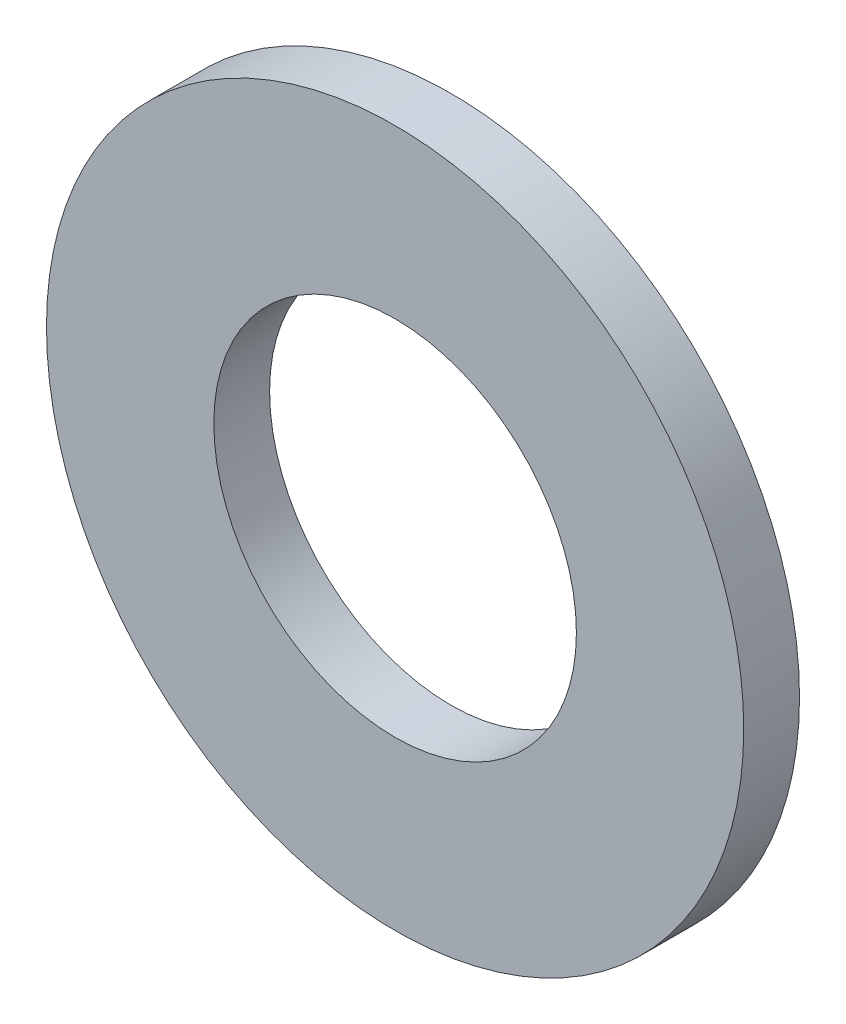
SolidWorks part; units mm, degrees
ref_plane "前视基准面" through (0, 0, 0) normal (0, 0, 1) x (1, 0, 0)
ref_plane "上视基准面" through (0, 0, 0) normal (0, 1, 0) x (1, 0, 0)
ref_plane "右视基准面" through (0, 0, 0) normal (1, 0, 0) x (0, 0, -1)
sketch "草图1" plane through (0, 0, 0) normal (0, 0, 1) x (1, 0, 0)
  circle A0 centre (0, 0) radius 12.5
  circle A1 centre (0, 0) radius 6.5
  dimension "D1" = 25
  dimension "D2" = 13
extrude "拉伸1" add sketch "草图1" along normal blind 2
